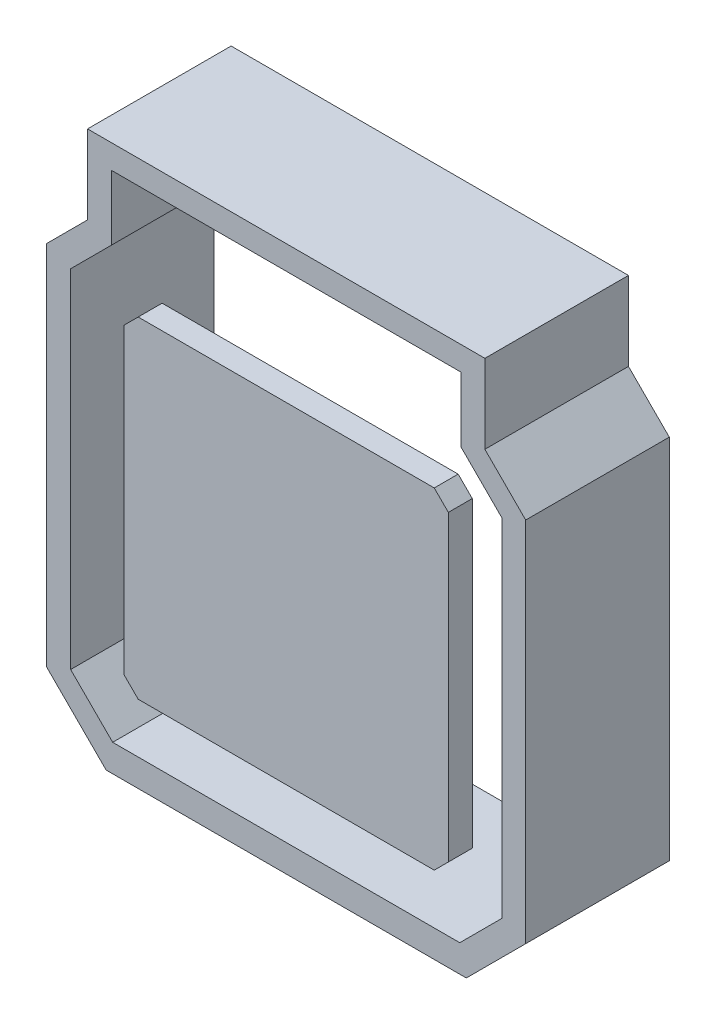
SolidWorks part; units mm, degrees
ref_plane "Alzado" through (0, 0, 0) normal (0, 0, 1) x (1, 0, 0)
ref_plane "Planta" through (0, 0, 0) normal (0, 1, 0) x (1, 0, 0)
ref_plane "Vista lateral" through (0, 0, 0) normal (1, 0, 0) x (0, 0, -1)
sketch "Croquis1" plane through (0, 0, 0) normal (0, 0, 1) x (1, 0, 0)
  line L0 (54.7517, 0) -> (-43.1835, 0) construction
  line L2 (-21.9073, 26.8767) -> (-27.0265, 21.7575)
  line L3 (-27.0265, 21.7575) -> (-27.0265, -21.7575)
  line L7 (27.0265, -21.7575) -> (27.0265, 21.7575)
  line L8 (27.0265, 21.7575) -> (21.9073, 26.8767)
  line L9 (21.9073, 30.45) -> (-21.9073, 30.45) construction
  line L10 (-24.9073, 28.1193) -> (-30.0265, 23.0001)
  line L11 (-30.0265, 23.0001) -> (-30.0265, -23.0001)
  line L12 (-30.0265, -23.0001) -> (-22.5766, -30.45)
  line L13 (-22.5766, -30.45) -> (22.5766, -30.45)
  line L14 (22.5766, -30.45) -> (30.0265, -23.0001)
  line L15 (30.0265, -23.0001) -> (30.0265, 23.0001)
  line L16 (30.0265, 23.0001) -> (24.9073, 28.1193)
  line L17 (-21.9073, 26.8767) -> (-21.9073, 35)
  line L18 (-21.9073, 35) -> (21.9073, 35)
  line L19 (21.9073, 35) -> (21.9073, 26.8767)
  line L20 (-24.9073, 28.1193) -> (-24.9073, 38)
  line L21 (-24.9073, 38) -> (24.9073, 38)
  line L22 (24.9073, 38) -> (24.9073, 28.1193)
  line L23 (21.334, 27.45) -> (-21.334, 27.45) construction
  line L24 (-21.334, 27.45) -> (-27.0265, 21.7575) construction
  line L25 (27.0265, 21.7575) -> (21.334, 27.45) construction
  line L26 (-22.5766, 30.45) -> (-30.0265, 23.0001) construction
  line L27 (22.5766, 30.45) -> (-22.5766, 30.45) construction
  line L28 (30.0265, 23.0001) -> (22.5766, 30.45) construction
  line L29 (-21.334, -27.45) -> (21.334, -27.45) construction
  line L30 (27.0265, -21.7575) -> (21.7575, -27.0265)
  line L31 (21.7575, -27.0265) -> (-21.7575, -27.0265)
  line L32 (-21.7575, -27.0265) -> (-27.0265, -21.7575)
  line L81 (-18.5587, 20.75) -> (-20.3265, 18.9822)
  line L82 (-20.3265, 18.9822) -> (-20.3265, -18.9822)
  line L83 (-20.3265, -18.9822) -> (-18.5587, -20.75)
  line L84 (-18.5587, -20.75) -> (18.5587, -20.75)
  line L85 (18.5587, -20.75) -> (20.3265, -18.9822)
  line L86 (20.3265, -18.9822) -> (20.3265, 18.9822)
  line L87 (20.3265, 18.9822) -> (18.5587, 20.75)
  line L88 (18.5587, 20.75) -> (-18.5587, 20.75)
  line L89 (0, 32.9128) -> (0, -32.9128) construction
  line L90 (21.334, -27.45) -> (27.0265, -21.7575) construction
  line L91 (-27.0265, -21.7575) -> (-21.334, -27.45) construction
  point P8 (0, 0)
  dimension "D1" = 40.653
  dimension "D2" = 41.5
  dimension "D3" = 135
  dimension "D4" = 135
  dimension "D5" = 135
  dimension "D6" = 135
  dimension "D7" = 2.5
  dimension "D8" = 2.5
  dimension "D9" = 2.5
  dimension "D10" = 2.5
  dimension "D13" = 43.8146
  dimension "D14" = 3
  dimension "D15" = 3
  dimension "D16" = 35
  dimension "D17" = 27.0265
  dimension "D18" = 135
  dimension "D11" = 6.7
  dimension "D12" = 3
extrude "Saliente-Extruir1" add sketch "Croquis1" against normal blind 3 contours L87 L88 L81 L82 L83 L84 L85 L86 | L16 L22 L21 L20 L10 L11 L12 L13 L14 L15 | L7 L8 L19 L18 L17 L2 L3 L32 L31 L30
sketch "Croquis2" plane through (0, 0, -3) normal (0, 0, -1) x (-1, 0, 0)
  line L1 (21.9073, 26.8767) -> (27.0265, 21.7575) construction
  line L2 (21.9073, 26.8767) -> (27.0265, 21.7575)
  line L3 (-20.3265, 18.9822) -> (-18.5587, 20.75)
  line L4 (-20.3265, 18.9822) -> (-18.5587, 20.75)
  line L5 (-18.5587, 20.75) -> (18.5587, 20.75)
  line L6 (-18.5587, 20.75) -> (18.5587, 20.75)
  line L7 (18.5587, 20.75) -> (20.3265, 18.9822)
  line L8 (18.5587, 20.75) -> (20.3265, 18.9822)
  line L9 (20.3265, 18.9822) -> (20.3265, -18.9822)
  line L10 (-30.0265, 23.0001) -> (-30.0265, -23.0001)
  line L11 (-30.0265, -23.0001) -> (-22.5766, -30.45)
  line L12 (-22.5766, -30.45) -> (22.5766, -30.45)
  line L13 (22.5766, -30.45) -> (30.0265, -23.0001)
  line L14 (30.0265, -23.0001) -> (30.0265, 23.0001)
  line L15 (30.0265, 23.0001) -> (24.9073, 28.1193)
  line L16 (24.9073, 28.1193) -> (24.9073, 38)
  line L17 (24.9073, 38) -> (-24.9073, 38)
  line L18 (-24.9073, 38) -> (-24.9073, 28.1193)
  line L19 (-24.9073, 28.1193) -> (-30.0265, 23.0001)
  line L20 (-30.0265, 23.0001) -> (-30.0265, -23.0001)
  line L21 (-30.0265, -23.0001) -> (-22.5766, -30.45)
  line L22 (-22.5766, -30.45) -> (22.5766, -30.45)
  line L23 (22.5766, -30.45) -> (30.0265, -23.0001)
  line L24 (30.0265, -23.0001) -> (30.0265, 23.0001)
  line L25 (30.0265, 23.0001) -> (24.9073, 28.1193)
  line L26 (24.9073, 28.1193) -> (24.9073, 38)
  line L27 (24.9073, 38) -> (-24.9073, 38)
  line L28 (-24.9073, 38) -> (-24.9073, 28.1193)
  line L29 (-24.9073, 28.1193) -> (-30.0265, 23.0001)
  line L30 (20.3265, 18.9822) -> (20.3265, -18.9822)
  line L31 (20.3265, -18.9822) -> (18.5587, -20.75)
  line L32 (20.3265, -18.9822) -> (18.5587, -20.75)
  line L33 (18.5587, -20.75) -> (-18.5587, -20.75)
  line L34 (18.5587, -20.75) -> (-18.5587, -20.75)
  line L35 (-18.5587, -20.75) -> (-20.3265, -18.9822)
  line L36 (-18.5587, -20.75) -> (-20.3265, -18.9822)
  line L37 (-20.3265, -18.9822) -> (-20.3265, 18.9822)
  line L38 (-20.3265, -18.9822) -> (-20.3265, 18.9822)
  line L39 (-30.0265, 23.0001) -> (-24.9073, 28.1193)
  line L40 (-30.0265, 23.0001) -> (-24.9073, 28.1193)
  line L41 (-24.9073, 28.1193) -> (-24.9073, 38)
  line L42 (-24.9073, 28.1193) -> (-24.9073, 38)
  line L43 (-24.9073, 38) -> (24.9073, 38)
  line L44 (-24.9073, 38) -> (24.9073, 38)
  line L45 (24.9073, 38) -> (24.9073, 28.1193)
  line L46 (24.9073, 38) -> (24.9073, 28.1193)
  line L47 (24.9073, 28.1193) -> (30.0265, 23.0001)
  line L48 (24.9073, 28.1193) -> (30.0265, 23.0001)
  line L49 (30.0265, 23.0001) -> (30.0265, -23.0001)
  line L50 (30.0265, 23.0001) -> (30.0265, -23.0001)
  line L51 (30.0265, -23.0001) -> (22.5766, -30.45)
  line L52 (30.0265, -23.0001) -> (22.5766, -30.45)
  line L53 (22.5766, -30.45) -> (-22.5766, -30.45)
  line L54 (22.5766, -30.45) -> (-22.5766, -30.45)
  line L55 (-22.5766, -30.45) -> (-30.0265, -23.0001)
  line L56 (-22.5766, -30.45) -> (-30.0265, -23.0001)
  line L57 (-30.0265, -23.0001) -> (-30.0265, 23.0001)
  line L58 (-30.0265, -23.0001) -> (-30.0265, 23.0001)
  line L59 (21.9073, 26.8767) -> (21.9073, 35) construction
  line L60 (21.9073, 26.8767) -> (21.9073, 35)
  line L61 (21.9073, 35) -> (-21.9073, 35) construction
  line L62 (21.9073, 35) -> (-21.9073, 35)
  line L63 (-21.9073, 35) -> (-21.9073, 26.8767) construction
  line L64 (-21.9073, 35) -> (-21.9073, 26.8767)
  line L65 (-27.0265, 21.7575) -> (-21.9073, 26.8767) construction
  line L66 (-27.0265, 21.7575) -> (-21.9073, 26.8767)
  line L67 (-27.0265, -21.7575) -> (-27.0265, 21.7575) construction
  line L68 (-27.0265, -21.7575) -> (-27.0265, 21.7575)
  line L69 (-27.0265, -21.7575) -> (-21.7575, -27.0265) construction
  line L70 (-27.0265, -21.7575) -> (-21.7575, -27.0265)
  line L71 (-21.7575, -27.0265) -> (21.7575, -27.0265) construction
  line L72 (-21.7575, -27.0265) -> (21.7575, -27.0265)
  line L73 (21.7575, -27.0265) -> (27.0265, -21.7575) construction
  line L74 (21.7575, -27.0265) -> (27.0265, -21.7575)
  line L75 (27.0265, 21.7575) -> (27.0265, -21.7575) construction
  line L76 (27.0265, 21.7575) -> (27.0265, -21.7575)
  line M11 (-30.0265, 23.0001) -> (-30.0265, -23.0001)
  line M12 (-30.0265, -23.0001) -> (-22.5766, -30.45)
  line M13 (-22.5766, -30.45) -> (22.5766, -30.45)
  line M14 (22.5766, -30.45) -> (30.0265, -23.0001)
  line M15 (30.0265, -23.0001) -> (30.0265, 23.0001)
  line M16 (30.0265, 23.0001) -> (24.9073, 28.1193)
  line M17 (24.9073, 28.1193) -> (24.9073, 38)
  line M18 (24.9073, 38) -> (-24.9073, 38)
  line M19 (-24.9073, 38) -> (-24.9073, 28.1193)
  line M20 (-24.9073, 28.1193) -> (-30.0265, 23.0001)
  line M21 (21.7575, -27.0265) -> (-21.7575, -27.0265)
  line M22 (-21.7575, -27.0265) -> (-27.0265, -21.7575)
  line M23 (-27.0265, -21.7575) -> (-27.0265, 21.7575)
  line M24 (-27.0265, 21.7575) -> (-21.9073, 26.8767)
  line M25 (-21.9073, 26.8767) -> (-21.9073, 35)
  line M26 (-21.9073, 35) -> (21.9073, 35)
  line M27 (21.9073, 35) -> (21.9073, 26.8767)
  line M28 (21.9073, 26.8767) -> (27.0265, 21.7575)
  line M29 (27.0265, 21.7575) -> (27.0265, -21.7575)
  line M30 (27.0265, -21.7575) -> (21.7575, -27.0265)
  dimension "D1" = 0
extrude "Saliente-Extruir3" add sketch "Croquis2" along normal blind 15 contours M20 M11 M12 M13 M14 M15 M16 M17 M18 M19 M30 M21 M22 M23 M24 M25 M26 M27 M28 M29
